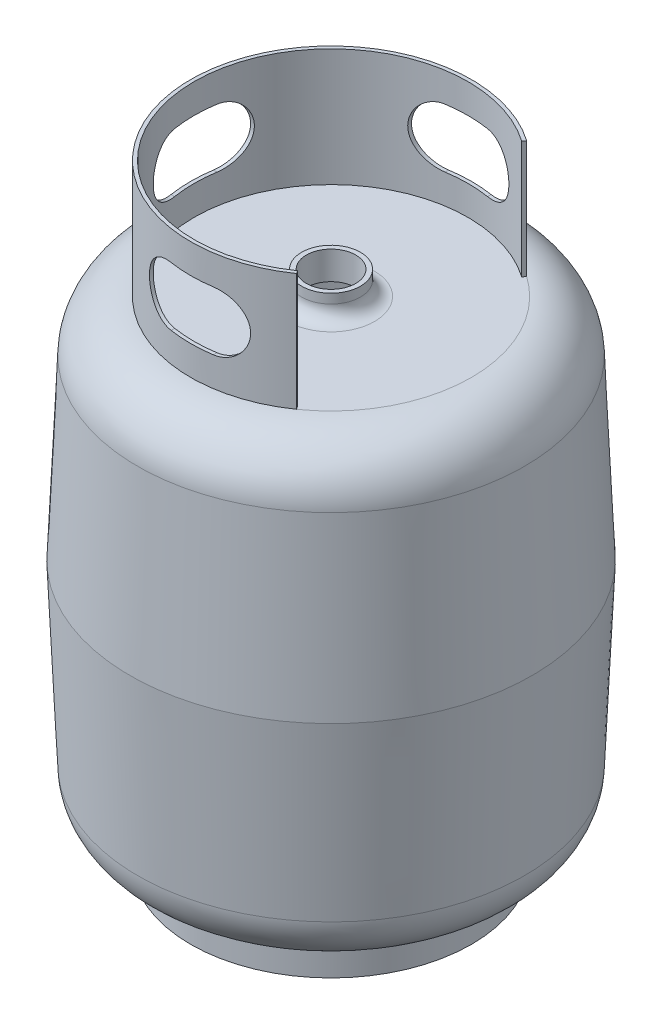
SolidWorks part; units mm, degrees
material "1060 Alloy"
ref_plane "Front Plane" through (0, 0, 0) normal (0, 0, 1) x (1, 0, 0)
ref_plane "Top Plane" through (0, 0, 0) normal (0, 1, 0) x (1, 0, 0)
ref_plane "Right Plane" through (0, 0, 0) normal (1, 0, 0) x (0, 0, -1)
sketch "Sketch1" plane through (0, 0, 0) normal (0, 0, 1) x (1, 0, 0)
  line L0 (0, 0) -> (119.4219, 0)
  line L1 (164.379, 43.0371) -> (170.9593, 193.75)
  line L2 (170.9593, 193.75) -> (164.379, 344.4629)
  line L3 (119.4219, 387.5) -> (25, 387.5)
  line L4 (0, 0) -> (0, 452.8327) construction
  line L5 (25, 387.5) -> (25, 407.5)
  line L6 (25, 407.5) -> (0, 407.5)
  line L7 (0, 4) -> (119.4219, 4)
  line L8 (160.3828, 43.2116) -> (166.9555, 193.75)
  line L9 (166.9555, 193.75) -> (160.3828, 344.2884)
  line L10 (119.4219, 383.5) -> (21, 383.5)
  line L11 (21, 383.5) -> (21, 403.5)
  line L12 (21, 403.5) -> (0, 403.5)
  line L13 (0, 403.5) -> (0, 407.5)
  line L14 (0, 4) -> (0, 0)
  arc A0 (119.4219, 0) -> (164.379, 43.0371) centre (119.4219, 45) ccw
  arc A1 (164.379, 344.4629) -> (119.4219, 387.5) centre (119.4219, 342.5) ccw
  arc A2 (119.4219, 4) -> (160.3828, 43.2116) centre (119.4219, 45) ccw
  arc A3 (160.3828, 344.2884) -> (119.4219, 383.5) centre (119.4219, 342.5) ccw
  point P10 (162.5, 0)
  point P14 (162.5, 387.5)
  dimension "D8" = 45
  dimension "D1" = 162.5
  dimension "D2" = 387.5
  dimension "D3" = 92.5
  dimension "D4" = 20
  dimension "D5" = 25
  dimension "D6" = 162.5
  dimension "D7" = 92.5
  dimension "D9" = 4
revolve "Revolve2" add sketch "Sketch1" angle 360 about L4
sketch "Sketch2" plane through (0, 387.5, 0) normal (0, 1, 0) x (1, 0, 0)
  circle A0 centre (0, 0) radius 21
  dimension "D1" = 42
extrude "Cut-Extrude3" cut sketch "Sketch2" along direction (0, 1, 0) on the side of the normal blind 140 and the other way blind 97
fillet "Fillet3" radius 12 1 edges at (0, 387.5, -25)
sketch "Sketch3" plane through (0, 0, 0) normal (0, -1, 0) x (1, 0, 0)
  circle A0 centre (0, 0) radius 116.4219
  circle A1 centre (0, 0) radius 119.4219
  circle A2 centre (0, 0) radius 119.4219
  circle A3 centre (0, 0) radius 131.4219 construction
  dimension "D2" = 3
  dimension "D1" = 0
  dimension "D3" = 12
extrude "Boss-Extrude1" add sketch "Sketch3" along normal blind 30
sketch "Sketch4" plane through (0, 387.5, 0) normal (0, 1, 0) x (1, 0, 0)
  line L0 (0, -230.2213) -> (0, 230.2213) construction
  line L1 (-227.6943, 0) -> (227.6943, 0) construction
  line L2 (0, 0) -> (107.0463, 152.878) construction
  line L3 (0, 0) -> (125.4368, -179.1423) construction
  line L4 (68.4976, 97.8247) -> (66.7768, 95.3672)
  line L5 (66.7768, -95.3672) -> (68.4976, -97.8247)
  circle A2 centre (0, 0) radius 116.4219
  arc A3 (66.7768, 95.3672) -> (66.7768, -95.3672) centre (0, 0) ccw
  circle A4 centre (0, 0) radius 119.4219 construction
  circle A5 centre (0, 0) radius 131.4219
  circle A6 centre (0, 0) radius 131.4219 construction
  arc A7 (68.4976, 97.8247) -> (68.4976, -97.8247) centre (0, 0) ccw
  point P2 (0, 0)
  point P14 (0, 0)
  dimension "D3" = 55
  dimension "D4" = 55
  dimension "D1" = 3
  dimension "D2" = 12
extrude "Boss-Extrude3" add sketch "Sketch4" along normal blind 100
sketch "Sketch6" plane through (0, 0, 0) normal (0, 0, 1) x (1, 0, 0)
  line L0 (0, -53.2775) -> (0, 505.3343) construction
  line L1 (-18, 437.5) -> (18, 437.5) construction
  line L2 (-18, 462.5) -> (18, 462.5)
  line L3 (-18, 412.5) -> (18, 412.5)
  line L4 (66.7768, 487.5) -> (-116.4219, 487.5) construction
  arc A0 (-18, 462.5) -> (-18, 412.5) centre (-18, 437.5) ccw
  arc A1 (18, 412.5) -> (18, 462.5) centre (18, 437.5) ccw
  point P5 (0, 437.5)
  dimension "D3" = 50
  dimension "D1" = 18
  dimension "D2" = 18
  dimension "D4" = 50
extrude "Cut-Extrude6" cut sketch "Sketch6" against normal through all both and the other way through all
sketch "Sketch8" plane through (0, 0, 0) normal (1, 0, 0) x (0, 0, -1)
  line L0 (0, -46.5645) -> (0, 569.1635) construction
  line L1 (-18, 437.5) -> (18, 437.5) construction
  line L2 (-18, 462.5) -> (18, 462.5)
  line L3 (-18, 412.5) -> (18, 412.5)
  line L4 (116.4219, 487.5) -> (-116.4219, 487.5) construction
  arc A0 (-18, 462.5) -> (-18, 412.5) centre (-18, 437.5) ccw
  arc A1 (18, 412.5) -> (18, 462.5) centre (18, 437.5) ccw
  point P5 (0, 437.5)
  dimension "D1" = 18
  dimension "D2" = 18
  dimension "D3" = 50
  dimension "D4" = 50
extrude "Cut-Extrude7" cut sketch "Sketch8" against normal through all both and the other way through all
equation "\"A\"= 325MM"
equation "\"B\"= 387.5MM"
